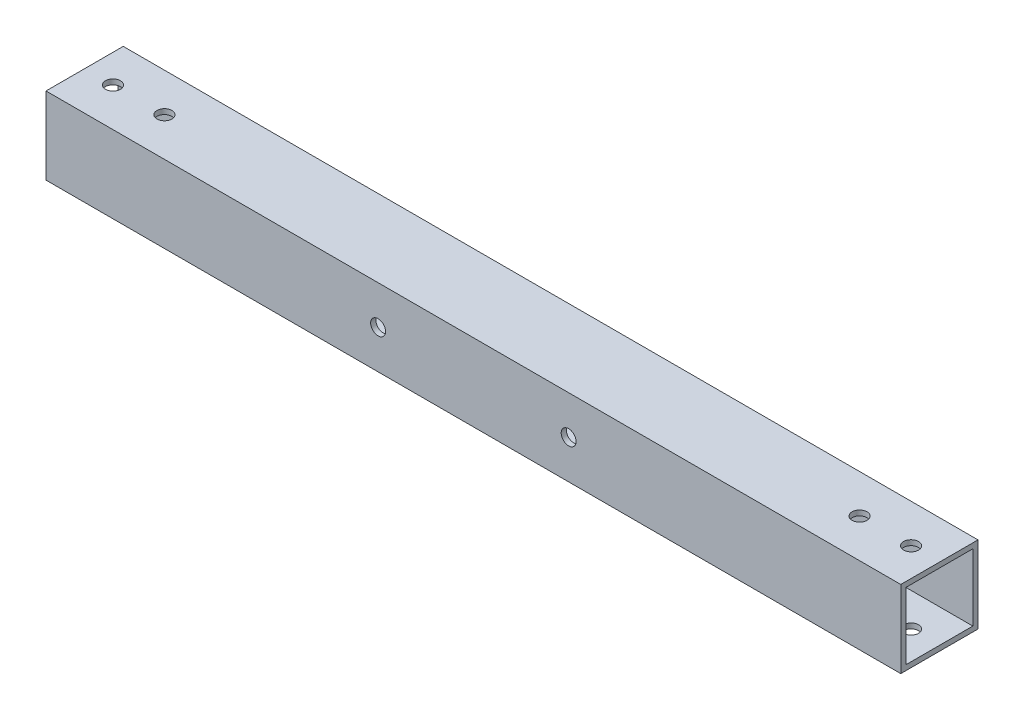
SolidWorks part; units mm, degrees
material "Thornel Mat VMA"
ref_plane "前视基准面" through (0, 0, 0) normal (0, 0, 1) x (1, 0, 0)
ref_plane "上视基准面" through (0, 0, 0) normal (0, 1, 0) x (1, 0, 0)
ref_plane "右视基准面" through (0, 0, 0) normal (1, 0, 0) x (0, 0, -1)
other "Configuration Table"
sketch "草图1" plane through (0, 0, 0) normal (0, 1, 0) x (1, 0, 0)
  line L0 (-83, 0) -> (83, 0)
  dimension "D1" = 166
other "铝管 15X15X1(1)"
ref_plane "基准面1" through (-83, 0, 0) normal (1, 0, 0) x (0, 0, -1)
sketch "草图11" plane through (-83, 0, 0) normal (1, 0, 0) x (0, 0, -1)
  line L1 (-7.5, -7.5) -> (7.5, -7.5)
  line L2 (-7.5, -7.5) -> (-7.5, 7.5)
  line L3 (-7.5, 7.5) -> (7.5, 7.5)
  line L4 (7.5, -7.5) -> (7.5, 7.5)
  line L5 (-7.5, -7.5) -> (7.5, 7.5) construction
  line L6 (-7.5, 7.5) -> (7.5, -7.5) construction
  line L7 (-6.5, -6.5) -> (6.5, -6.5)
  line L8 (-6.5, -6.5) -> (-6.5, 6.5)
  line L9 (-6.5, 6.5) -> (6.5, 6.5)
  line L10 (6.5, -6.5) -> (6.5, 6.5)
  line L11 (-6.5, -6.5) -> (6.5, 6.5) construction
  line L12 (-6.5, 6.5) -> (6.5, -6.5) construction
  point P0 (0, 0)
  point P6 (0, 0)
  point P11 (0, 0)
  dimension "D1" = 15
  dimension "D2" = 15
  dimension "D3" = 13
  dimension "D4" = 13
sketch "草图12" plane through (0, 0, -7.5) normal (0, 0, -1) x (-1, 0, 0)
  line L0 (83, 0) -> (-83, 0) construction
  circle A0 centre (-18.5, 0) radius 1.45
  circle A1 centre (18.5, 0) radius 1.45
  point P9 (17.0499, 3.8722)
  dimension "D1" = 2.9
  dimension "D2" = 2.9
  dimension "D3" = 18.5
  dimension "D4" = 18.5
extrude "切除-拉伸1" cut sketch "草图12" against normal through all
sketch "草图13" plane through (0, -7.5, 0) normal (0, -1, 0) x (1, 0, 0)
  line L0 (-83, 0) -> (83, 0) construction
  line L1 (-83, 7.5) -> (-83, -7.5) construction
  line L2 (0, 7.5) -> (0, -7.5) construction
  line L3 (83, 7.5) -> (-83, 7.5) construction
  line L4 (83, -7.5) -> (-83, -7.5) construction
  circle A0 centre (-77.5, 0) radius 1.45
  circle A1 centre (-67.5, 0) radius 1.45
  circle A2 centre (67.5, 0) radius 1.45
  circle A3 centre (77.5, 0) radius 1.45
  dimension "D1" = 2.9
  dimension "D2" = 2.9
  dimension "D4" = 10
  dimension "D3" = 5.5
extrude "切除-拉伸2" cut sketch "草图13" against normal through all
